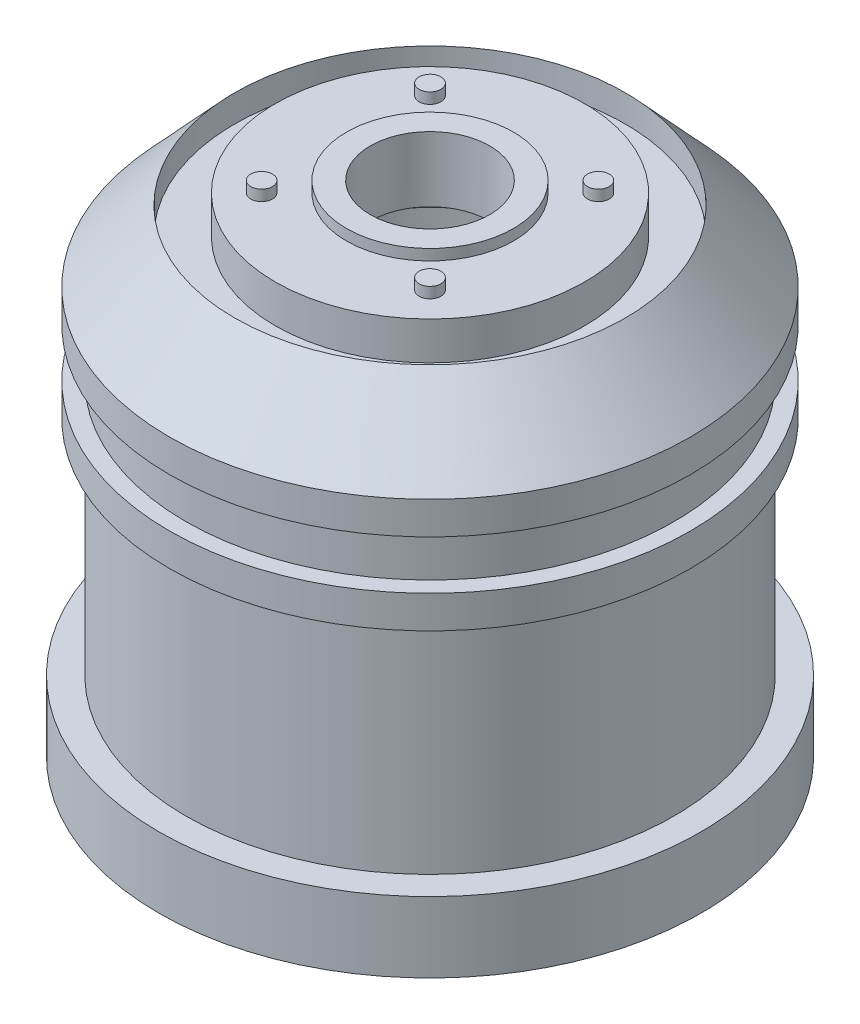
SolidWorks part; units mm, degrees
material "PVC Rigid"
ref_plane "Front Plane" through (0, 0, 0) normal (0, 0, 1) x (1, 0, 0)
ref_plane "Top Plane" through (0, 0, 0) normal (0, 1, 0) x (1, 0, 0)
ref_plane "Right Plane" through (0, 0, 0) normal (1, 0, 0) x (0, 0, -1)
sketch "Sketch1" plane through (0, 0, 0) normal (0, 1, 0) x (1, 0, 0)
  circle A0 centre (0, 0) radius 12.7
  dimension "D1" = 25.4
extrude "Bottom_Lip" add sketch "Sketch1" along normal blind 3.302
sketch "Sketch2" plane through (0, 3.302, 0) normal (0, 1, 0) x (1, 0, 0)
  circle A0 centre (0, 0) radius 11.43
  dimension "D1" = 22.86
extrude "Boss-Extrude3" add sketch "Sketch2" along normal blind 10.414 contours A0
sketch "Sketch3" plane through (0, 13.716, 0) normal (0, 1, 0) x (1, 0, 0)
  circle A0 centre (0, 0) radius 12.192
extrude "Boss-Extrude4" add sketch "Sketch3" along normal blind 1.524
sketch "Sketch4" plane through (0, 15.24, 0) normal (0, 1, 0) x (1, 0, 0)
  circle A0 centre (0, 0) radius 11.43
extrude "Boss-Extrude5" add sketch "Sketch4" along normal blind 2.286
sketch "Sketch5" plane through (0, 17.526, 0) normal (0, 1, 0) x (1, 0, 0)
  circle A0 centre (0, 0) radius 12.192
extrude "Boss-Extrude7" add sketch "Sketch5" along normal blind 1.524 contours A0
sketch "Sketch6" plane through (0, 19.05, 0) normal (0, 1, 0) x (1, 0, 0)
  circle A0 centre (0, 0) radius 12.192
extrude "Boss-Extrude8" add sketch "Sketch6" along normal blind 3.302 draft 42.727 separate body
sketch "Sketch12" plane through (0, 22.352, 0) normal (0, 1, 0) x (1, 0, 0)
  circle A0 centre (0, 0) radius 7.239
  dimension "D1" = 14.478
extrude "Boss-Extrude9" add sketch "Sketch12" along normal blind 0.508
sketch "Sketch13" plane through (0, 22.352, 0) normal (0, 1, 0) x (1, 0, 0)
  circle A0 centre (0, 0) radius 9.1421
extrude "Cut-Extrude2" cut sketch "Sketch13" against normal blind 1.27 from offset 0
sketch "Sketch14" plane through (0, 21.082, 0) normal (0, 1, 0) x (1, 0, 0)
  circle A0 centre (0, 0) radius 7.239
extrude "Boss-Extrude10" add sketch "Sketch14" along normal blind 1.778
sketch "Sketch15" plane through (0, 22.86, 0) normal (0, 1, 0) x (1, 0, 0)
  circle A0 centre (0, 0) radius 2.794
  dimension "D1" = 5.588
extrude "Cut-Extrude3" cut sketch "Sketch15" against normal through all and the other way through all
sketch "Sketch16" plane through (0, 0, 0) normal (0, -1, 0) x (1, 0, 0)
  circle A0 centre (0, 0) radius 9.525
extrude "Cut-Extrude4" cut sketch "Sketch16" against normal blind 20.32
sketch "Sketch17" plane through (0, 20.32, 0) normal (0, -1, 0) x (1, 0, 0)
  circle A0 centre (0, 0) radius 7.239
  circle A1 centre (0, 0) radius 6.35
extrude "Boss-Extrude11" add sketch "Sketch17" along normal blind 2.54
sketch "Sketch18" plane through (0, 22.86, 0) normal (0, 1, 0) x (1, 0, 0)
  circle A0 centre (0, 0) radius 3.9111
  dimension "D1" = 7.8223
extrude "Boss-Extrude15" add sketch "Sketch18" along normal through all from offset 0.508 contours A0
sketch "Sketch19" plane through (0, 23.368, 0) normal (0, 1, 0) x (1, 0, 0)
  circle A0 centre (0, 0) radius 2.794
extrude "Cut-Extrude5" cut sketch "Sketch19" against normal through all
sketch "Sketch20" plane through (0, 22.86, 0) normal (0, 1, 0) x (1, 0, 0)
  line L0 (0, 0) -> (18.2356, 0) construction
  line L1 (18.2356, 0) -> (-17.296, 0) construction
  line L2 (0, 0) -> (0, 14.4164) construction
  line L3 (0, 14.4164) -> (0, -15.6737) construction
  line L4 (3.942, -3.942) -> (0, 0) construction
  line L5 (2.7656, -2.7656) -> (6.36, 0.8288) construction
  line L6 (3.942, -3.942) -> (5.4963, -4.7111) construction
  line L7 (5.4963, -4.7111) -> (7.8273, 0) construction
  line L9 (0, 0) -> (-3.942, -3.942) construction
  circle A0 centre (3.942, -3.942) radius 0.508
  circle A1 centre (0, 0) radius 3.9111 construction
  circle A3 centre (0, 0) radius 7.239 construction
  circle A7 centre (-3.942, -3.942) radius 0.508
  circle A12 centre (-3.942, 3.942) radius 0.508
  circle A13 centre (3.942, 3.942) radius 0.508
  dimension "D1" = 1.6637
  dimension "D2" = 45
  dimension "D3" = 4
extrude "Boss-Extrude16" add sketch "Sketch20" along normal blind 0.508
